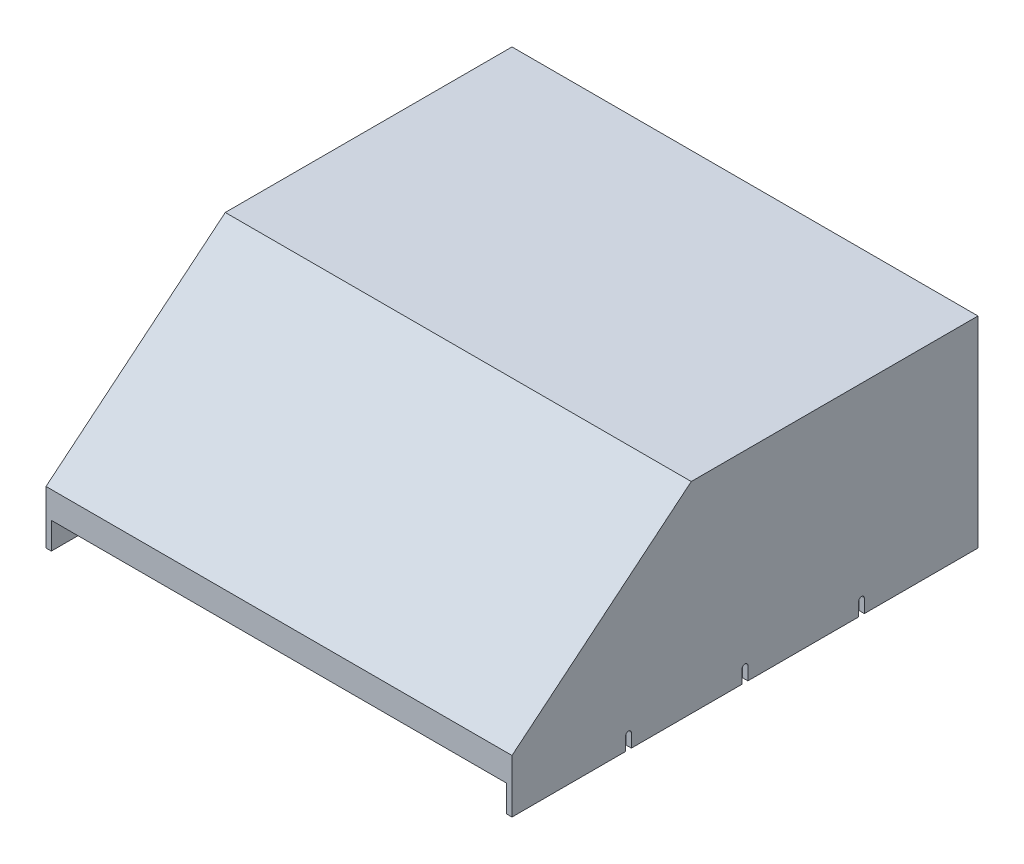
SolidWorks part; units mm, degrees
material "ABS PC generico"
ref_plane "Piano frontale" through (0, 0, 0) normal (0, 0, 1) x (1, 0, 0)
ref_plane "Piano superiore" through (0, 0, 0) normal (0, 1, 0) x (1, 0, 0)
ref_plane "Piano destro" through (0, 0, 0) normal (1, 0, 0) x (0, 0, -1)
sketch "Schizzo1" plane through (0, 0, 0) normal (1, 0, 0) x (0, 0, -1)
  line L0 (524, 0) -> (524, 226)
  line L2 (0, 60) -> (201.5761, 226)
  line L3 (524, 226) -> (201.5761, 226)
  line L4 (0, 60) -> (0, 0)
  line L5 (0, 0) -> (524, 0)
  point P4 (160, 226)
  dimension "D1" = 524
extrude "Estrusione-Estrusione1" add sketch "Schizzo1" along normal blind 524
shell "Svuota1" thickness 6
sketch "Schizzo2" plane through (0, 0, 0) normal (0, -1, 0) x (1, 0, 0)
  line L0 (518, -6) -> (518, 0)
  line L1 (524, 0) -> (0, 0) construction
  line L2 (6, -6) -> (6, 0)
  line L3 (6, -6) -> (518, -6)
  line L4 (518, 0) -> (6, 0)
extrude "Taglio-Estrusione1" cut sketch "Schizzo2" against normal blind 30
sketch "Schizzo3" plane through (0, 0, 0) normal (0, -1, 0) x (1, 0, 0)
  line L0 (518, -518) -> (518, -524)
  line L1 (524, -524) -> (0, -524) construction
  line L2 (6, -518) -> (6, -524)
  line L3 (518, -524) -> (6, -524)
  line L4 (518, -518) -> (6, -518)
extrude "Taglio-Estrusione2" cut sketch "Schizzo3" against normal blind 80
sketch "Schizzo4" plane through (0, 0, 0) normal (-1, 0, 0) x (0, 0, 1)
  line L11 (-396.25, 15) -> (-396.25, 0)
  line L12 (-524, 0) -> (96.556, 0) construction
  line L13 (0, 25.6095) -> (0, -48.2106) construction
  line L14 (0, 60) -> (0, 0) construction
  line L15 (-262, 0) -> (-262, 99.4297) construction
  line L16 (-389.75, 15) -> (-389.75, 0)
  line L17 (-131, 15) -> (-131, 0) construction
  line L18 (-201.5761, 226) -> (-201.5761, -62.9747) construction
  line L19 (-393, 15) -> (-393, 0) construction
  line L20 (-265.25, 15) -> (-265.25, 0)
  line L21 (-134.25, 0) -> (-127.75, 0)
  line L22 (-265.25, 0) -> (-258.75, 0)
  line L23 (-134.25, 15) -> (-134.25, 0)
  line L24 (-127.75, 15) -> (-127.75, 0)
  line L25 (-396.25, 15) -> (-396.25, -70.3567) construction
  line L26 (-389.75, 15) -> (-389.75, -70.3567) construction
  line L27 (-393, 15) -> (-393, -70.3567) construction
  line L28 (-262, 15) -> (-262, 0) construction
  line L29 (-396.25, 0) -> (-389.75, 0)
  line L31 (-258.75, 15) -> (-258.75, 0)
  arc A2 (-134.25, 15) -> (-127.75, 15) centre (-131, 15) cw
  arc A3 (-265.25, 15) -> (-258.75, 15) centre (-262, 15) cw
  arc A4 (-396.25, 15) -> (-389.75, 15) centre (-393, 15) cw
  point P21 (186.4358, 0)
  point P24 (-524, 15)
  point P25 (186.4358, 15)
  dimension "D1" = 6.5
  dimension "D3" = 3.25
  dimension "D4" = 3.25
extrude "Taglio-Estrusione3" cut sketch "Schizzo4" against normal through all
